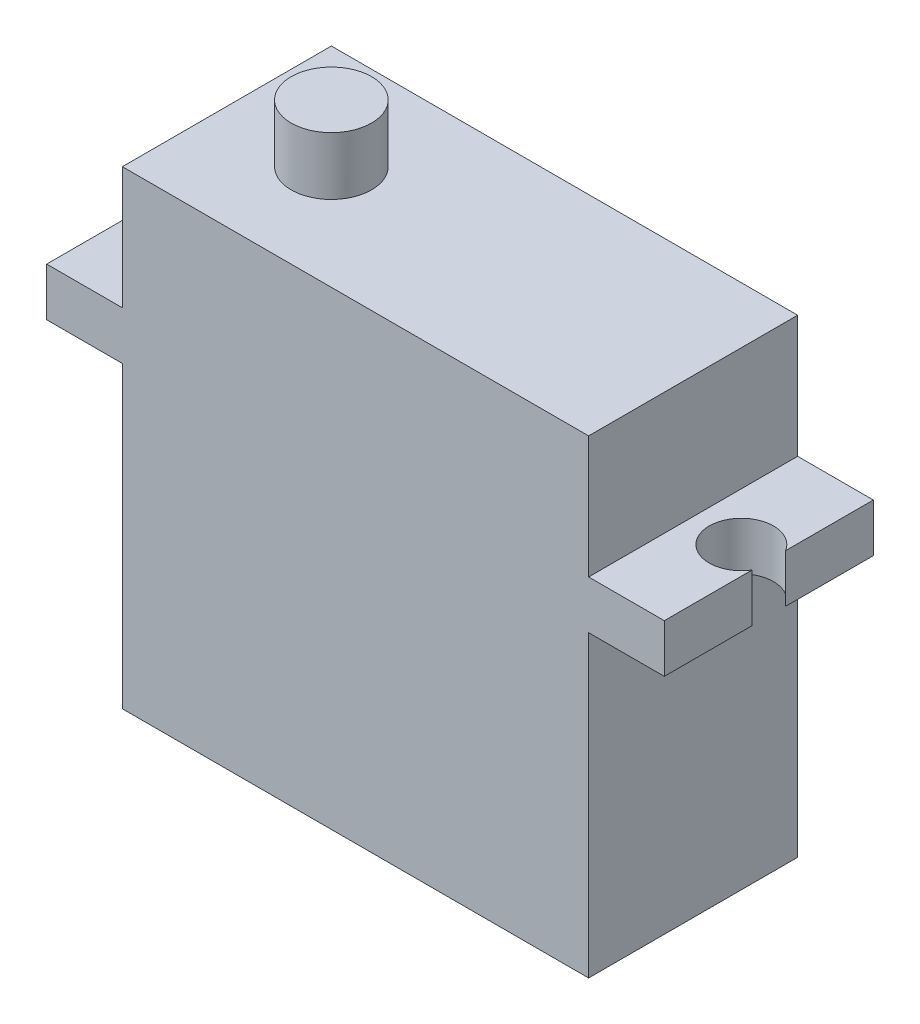
SolidWorks part; units mm, degrees
ref_plane "前视基准面" through (0, 0, 0) normal (0, 0, 1) x (1, 0, 0)
ref_plane "上视基准面" through (0, 0, 0) normal (0, 1, 0) x (1, 0, 0)
ref_plane "右视基准面" through (0, 0, 0) normal (1, 0, 0) x (0, 0, -1)
other "Configuration Table"
sketch "草图1" plane through (0, 0, 0) normal (0, 1, 0) x (1, 0, 0)
  line L1 (0, 0) -> (29, 0)
  line L2 (0, 0) -> (0, 13)
  line L3 (0, 13) -> (29, 13)
  line L4 (29, 0) -> (29, 13)
  dimension "D1" = 29
  dimension "D2" = 13
extrude "凸台-拉伸2" add sketch "草图1" along normal blind 29.2
ref_plane "基准面1" through (0, 18.6, 0) normal (0, -1, 0) x (-1, 0, 0)
sketch "草图2" plane through (0, 18.6, 0) normal (0, -1, 0) x (-1, 0, 0)
  line L0 (-29, 6.5) -> (0, 6.5) construction
  line L1 (-32, 6.5) -> (3, 6.5) construction
  line L2 (-14.5, 6.5) -> (-14.5, 13) construction
  line L3 (-29, 13) -> (-33.7065, 13)
  line L4 (0, 0) -> (0, 13)
  line L5 (0, 13) -> (-29, 13)
  line L6 (-29, 13) -> (-29, 0)
  line L7 (-29, 0) -> (0, 0)
  line L8 (0, 0) -> (0, 13)
  line L9 (0, 13) -> (-29, 13)
  line L10 (-29, 13) -> (-29, 0)
  line L11 (-29, 0) -> (0, 0)
  line L12 (-29, 13) -> (-29, 0)
  line L13 (-29, 0) -> (-33.7065, 0)
  line L14 (-33.7065, 13) -> (-33.7065, 0)
  line L15 (0, 13) -> (4.7065, 13)
  line L16 (0, 0) -> (4.7065, 0)
  line L17 (4.7065, 13) -> (4.7065, 0)
  circle A0 centre (-32, 6.5) radius 2
  circle A1 centre (3, 6.5) radius 2
  point P9 (-14.5, 6.5)
  dimension "D1" = 0
extrude "凸台-拉伸3" add sketch "草图2" against normal blind 3 contours A1 L17 L15 L8 L16 | A0 L14 L13 L10 L3
sketch "草图3" plane through (0, 29.2, 0) normal (0, 1, 0) x (1, 0, 0)
  line L0 (0, 6.5) -> (29, 6.5) construction
  line L2 (0, 13) -> (6.5, 13)
  line L3 (0, 13) -> (0, 0)
  line L4 (0, 13) -> (0, 0)
  line L5 (0, 0) -> (29, 0)
  line L6 (29, 0) -> (29, 13)
  line L7 (29, 13) -> (0, 13)
  line L8 (0, 13) -> (0, 0)
  line L9 (0, 0) -> (29, 0)
  line L10 (29, 0) -> (29, 13)
  line L11 (29, 13) -> (0, 13)
  line L12 (0, 0) -> (6.5, 0)
  line L13 (6.5, 13) -> (6.5, 0)
  line L14 (0, 13) -> (6.5, 0) construction
  line L15 (0, 0) -> (6.5, 13) construction
  circle A0 centre (6.5, 6.5) radius 6.5
  circle A1 centre (6.5, 6.5) radius 2.5
  point P9 (3.25, 6.5)
  dimension "D1" = 0
extrude "凸台-拉伸4" add sketch "草图3" along normal blind 3.6 contours L13 A1 | L13 A1
